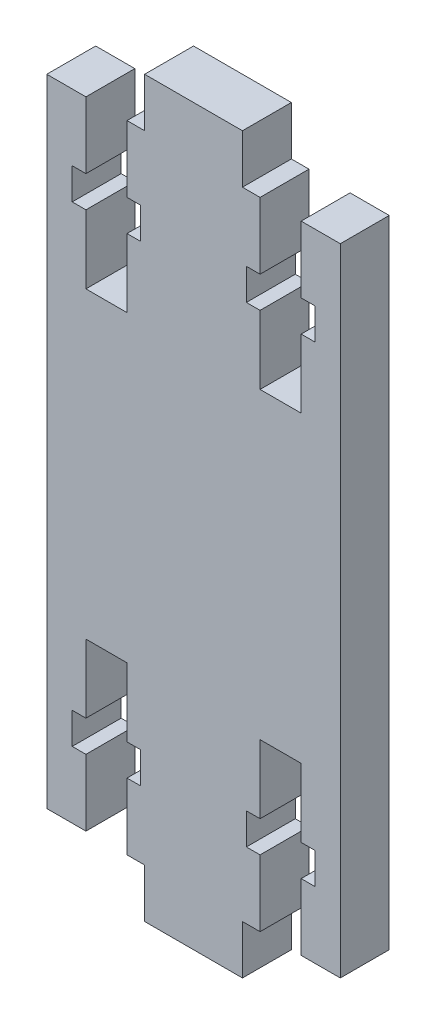
SolidWorks part; units mm, degrees
ref_plane "Front Plane" through (0, 0, 0) normal (0, 0, 1) x (1, 0, 0)
ref_plane "Top Plane" through (0, 0, 0) normal (0, 1, 0) x (1, 0, 0)
ref_plane "Right Plane" through (0, 0, 0) normal (1, 0, 0) x (0, 0, -1)
sketch "Sketch1" plane through (0, 0, 0) normal (0, 0, 1) x (1, 0, 0)
  line L0 (-15, 65) -> (-15, 56.3298) construction
  line L1 (0, 0) -> (-30, 0)
  line L2 (0, 0) -> (0, 65)
  line L3 (0, 65) -> (-30, 65)
  line L4 (-30, 0) -> (-30, 65)
  line L5 (-20, 65) -> (-10, 65)
  line L6 (-20, 65) -> (-20, 70)
  line L7 (-20, 70) -> (-10, 70)
  line L8 (-10, 65) -> (-10, 70)
  line L9 (-20, 0) -> (-10, 0)
  line L10 (-20, 0) -> (-20, -5)
  line L11 (-20, -5) -> (-10, -5)
  line L12 (-10, 0) -> (-10, -5)
  line L13 (-26, 65) -> (-21.8, 65)
  line L14 (-26, 65) -> (-26, 48)
  line L15 (-26, 48) -> (-21.8, 48)
  line L16 (-21.8, 65) -> (-21.8, 48)
  line L17 (-27.4, 58.2) -> (-20.4, 58.2)
  line L18 (-27.4, 58.2) -> (-27.4, 55)
  line L19 (-27.4, 55) -> (-20.4, 55)
  line L20 (-20.4, 58.2) -> (-20.4, 55)
  line L21 (-9.6, 58.2) -> (-9.6, 55)
  line L22 (-2.6, 55) -> (-9.6, 55)
  line L23 (-2.6, 58.2) -> (-2.6, 55)
  line L24 (-2.6, 58.2) -> (-9.6, 58.2)
  line L25 (-8.2, 65) -> (-8.2, 48)
  line L26 (-4, 48) -> (-8.2, 48)
  line L27 (-4, 65) -> (-4, 48)
  line L28 (-4, 65) -> (-8.2, 65)
  line L29 (-30, 32.5) -> (-11.9736, 32.5) construction
  line L30 (-15, 0) -> (-15, 8.6702) construction
  line L31 (-4, 0) -> (-8.2, 0)
  line L32 (-4, 0) -> (-4, 17)
  line L33 (-4, 17) -> (-8.2, 17)
  line L34 (-8.2, 0) -> (-8.2, 17)
  line L35 (-2.6, 6.8) -> (-9.6, 6.8)
  line L36 (-2.6, 6.8) -> (-2.6, 10)
  line L37 (-2.6, 10) -> (-9.6, 10)
  line L38 (-9.6, 6.8) -> (-9.6, 10)
  line L39 (-20.4, 6.8) -> (-20.4, 10)
  line L40 (-27.4, 10) -> (-20.4, 10)
  line L41 (-27.4, 6.8) -> (-27.4, 10)
  line L42 (-27.4, 6.8) -> (-20.4, 6.8)
  line L43 (-21.8, 0) -> (-21.8, 17)
  line L44 (-26, 17) -> (-21.8, 17)
  line L45 (-26, 0) -> (-26, 17)
  line L46 (-26, 0) -> (-21.8, 0)
  point P21 (-23.9, 55)
  point P22 (-23.9, 48)
  dimension "D1" = 5
  dimension "D2" = 5
  dimension "D3" = 65
  dimension "D4" = 10
  dimension "D5" = 10
  dimension "D6" = 10
  dimension "D7" = 10
  dimension "D8" = 10
  dimension "D9" = 6.8
  dimension "D10" = 7
  dimension "D11" = 4.2
  dimension "D12" = 3.2
  dimension "D13" = 4
  dimension "D14" = 17
extrude "Boss-Extrude1" add sketch "Sketch1" along normal blind 5 contours L1 L45 L42 L41 L40 L44 L43 L39 L34 L35 L38 L37 L33 L32 L36 L2 L3 L27 L24 L23 L22 L26 L25 L21 L16 L17 L20 L19 L15 L14 | L3 L8 L7 L6 | L12 L1 L10 L11
